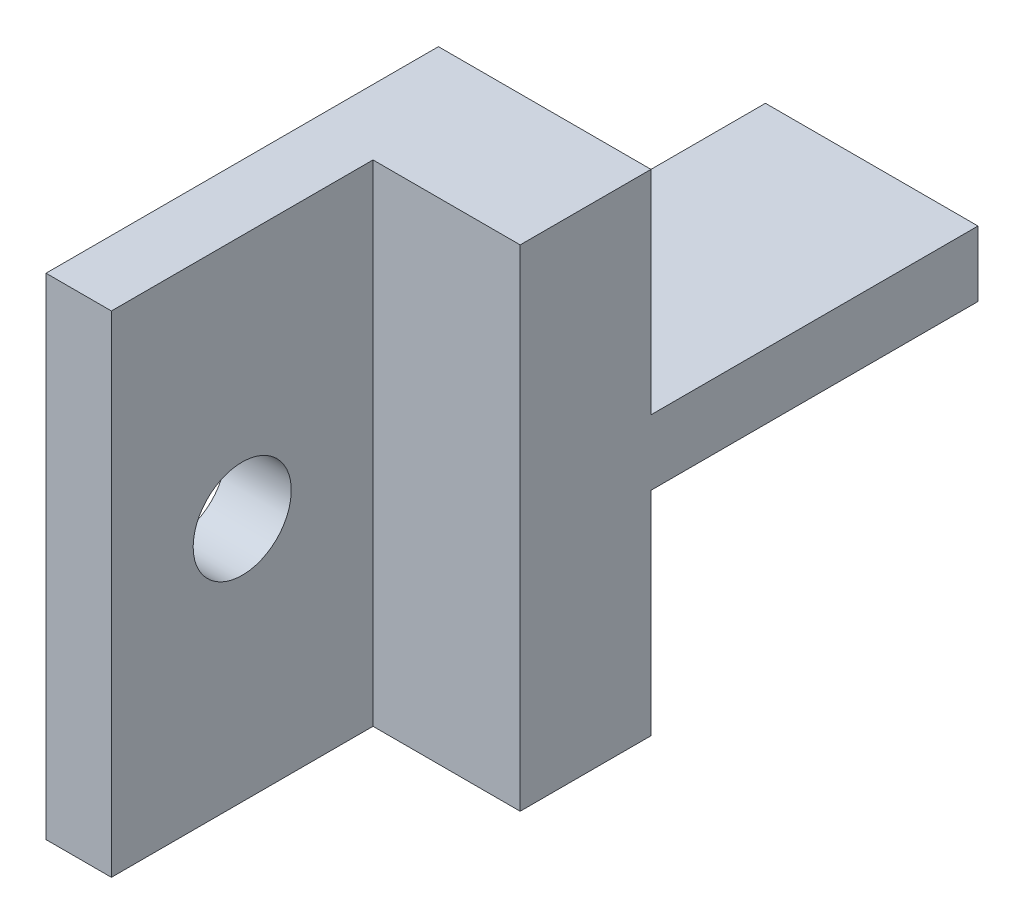
SolidWorks part; units mm, degrees
ref_plane "Front Plane" through (0, 0, 0) normal (0, 0, 1) x (1, 0, 0)
ref_plane "Top Plane" through (0, 0, 0) normal (0, 1, 0) x (1, 0, 0)
ref_plane "Right Plane" through (0, 0, 0) normal (1, 0, 0) x (0, 0, -1)
sketch "Sketch1" plane through (0, 0, 0) normal (1, 0, 0) x (0, 0, -1)
  line L1 (0, 0) -> (30, 0)
  line L2 (0, 0) -> (0, 15)
  line L3 (0, 15) -> (30, 15)
  line L4 (30, 0) -> (30, 15)
  dimension "D1" = 15
  dimension "D2" = 30
extrude "Boss-Extrude1" add sketch "Sketch1" along normal blind 2
sketch "Sketch2" plane through (0, 0, -30) normal (0, 0, -1) x (-1, 0, 0)
  line L1 (0, 15) -> (-6.5, 15)
  line L2 (0, 15) -> (0, 0)
  line L3 (0, 0) -> (-6.5, 0)
  line L4 (-6.5, 15) -> (-6.5, 0)
  dimension "D1" = 6.5
extrude "Boss-Extrude2" add sketch "Sketch2" along normal blind 4
sketch "Sketch3" plane through (0, 0, -34) normal (0, 0, -1) x (-1, 0, 0)
  line L0 (-6.5, 15) -> (-6.5, 0) construction
  line L1 (-6.5, 8.5) -> (0, 8.5)
  line L2 (-6.5, 8.5) -> (-6.5, 6.5)
  line L3 (-6.5, 6.5) -> (0, 6.5)
  line L4 (0, 8.5) -> (0, 6.5)
  line L5 (0, 0) -> (0, 15) construction
  point P8 (-6.5, 7.5)
  dimension "D1" = 2
  dimension "D2" = 7.5
extrude "Boss-Extrude3" add sketch "Sketch3" along normal blind 10
sketch "Sketch4" plane through (2, 0, 0) normal (1, 0, 0) x (0, 0, -1)
  circle A0 centre (10, 7.5) radius 2
  dimension "D2" = 4
  dimension "D1" = 20
extrude "Cut-Extrude2" cut sketch "Sketch4" against normal blind 5 contours A0
sketch "Sketch5" plane through (2, 0, 0) normal (1, 0, 0) x (0, 0, -1)
  circle A0 centre (10, 7.5) radius 2
  circle A1 centre (10, 7.5) radius 3.5
  circle A2 centre (10, 7.5) radius 2
  circle M1 centre (10, 7.5) radius 2
  dimension "D1" = 7
extrude "Boss-Extrude4" add sketch "Sketch5" along normal blind 5 contours A1 M1
sketch "Sketch6" plane through (0, 0, 0) normal (-1, 0, 0) x (0, 0, 1)
  line L0 (0, 0) -> (-34, 0) construction
  line L1 (0, 15) -> (-22, 15)
  line L2 (0, 15) -> (0, 0)
  line L3 (0, 0) -> (-22, 0)
  line L4 (-22, 15) -> (-22, 0)
  dimension "D1" = 12
extrude "Cut-Extrude3" cut sketch "Sketch6" against normal blind 10
sketch "Sketch7" plane through (0, 0, 0) normal (-1, 0, 0) x (0, 0, 1)
  circle A0 centre (-26, 7.5) radius 1.5
  dimension "D1" = 3
  dimension "D2" = 4
extrude "Cut-Extrude4" cut sketch "Sketch7" against normal blind 10
